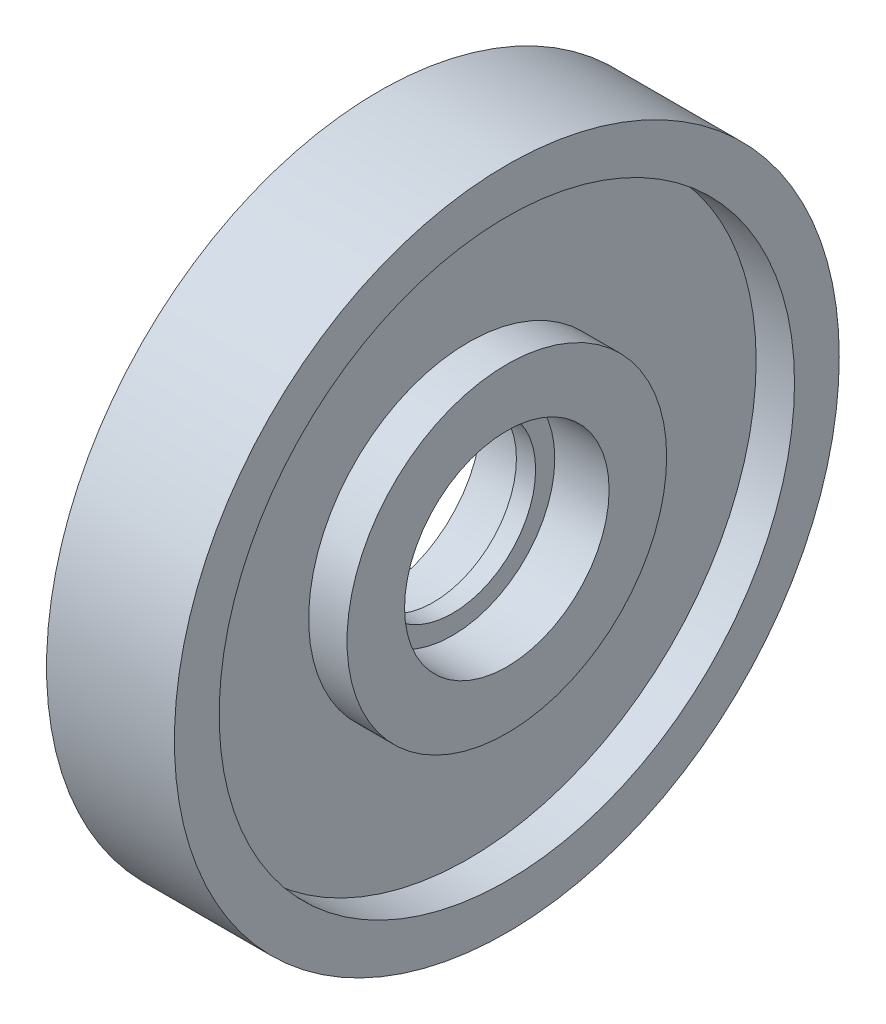
SolidWorks part; units mm, degrees
material "2024-T4"
ref_plane "Front Plane" through (0, 0, 0) normal (0, 0, 1) x (1, 0, 0)
ref_plane "Top Plane" through (0, 0, 0) normal (0, 1, 0) x (1, 0, 0)
ref_plane "Right Plane" through (0, 0, 0) normal (1, 0, 0) x (0, 0, -1)
sketch "Sketch1" plane through (0, 0, 0) normal (1, 0, 0) x (0, 0, -1)
  circle A0 centre (0, 0) radius 26
  circle A2 centre (0, 0) radius 8
  dimension "D1" = 52
  dimension "D2" = 16
extrude "Boss-Extrude1" add sketch "Sketch1" along normal blind 10
ref_plane "Plane1" through (5, 0, 0) normal (1, 0, 0) x (0, 0, -1)
sketch "Sketch2" plane through (5, 0, 0) normal (1, 0, 0) x (0, 0, -1)
  circle A0 centre (0, 0) radius 6.5
  circle A1 centre (0, 0) radius 8 construction
  circle A2 centre (0, 0) radius 8
  dimension "D1" = 13
extrude "Boss-Extrude2" add sketch "Sketch2" along normal mid plane 1.5
sketch "Sketch3" plane through (10, 0, 0) normal (1, 0, 0) x (0, 0, -1)
  circle A0 centre (0, 0) radius 22.5
  circle A1 centre (0, 0) radius 12.5
  dimension "D1" = 25
  dimension "D2" = 45
extrude "Cut-Extrude1" cut sketch "Sketch3" against normal blind 3
ref_plane "Plane2" through (5, 0, 0) normal (1, 0, 0) x (0, 0, -1)
mirror "Mirror1" about plane through (5, 0, 0) normal (1, 0, 0) of "Cut-Extrude1"
